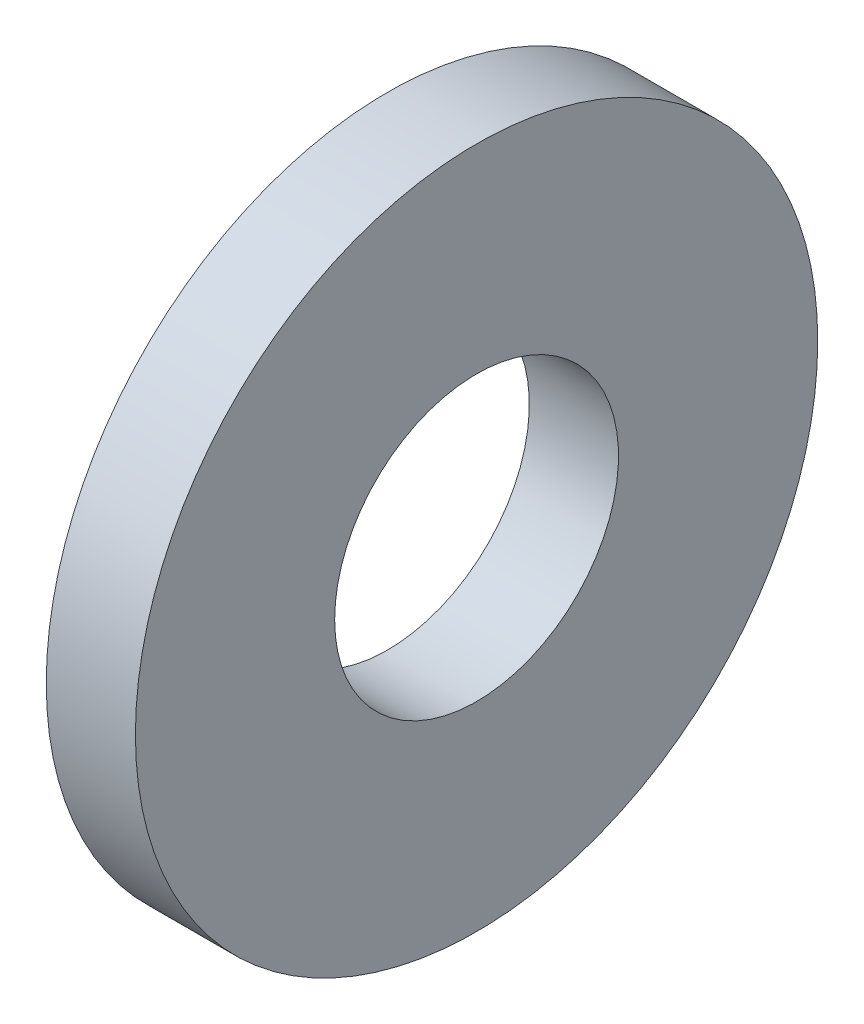
SolidWorks part; units mm, degrees
ref_plane "Plane1" through (0, 0, 0) normal (0, 0, 1) x (1, 0, 0)
ref_plane "Plane2" through (0, 0, 0) normal (0, 1, 0) x (1, 0, 0)
ref_plane "Plane3" through (0, 0, 0) normal (1, 0, 0) x (0, 0, -1)
sketch "Sketch1" plane through (0, 0, 0) normal (0, 0, 1) x (1, 0, 0)
  line L0 (-34.925, 0) -> (9.525, 0) construction
  line L1 (0, 1.9812) -> (0, 4.7625)
  line L2 (0, 4.7625) -> (-1.2446, 4.7625)
  line L3 (-1.2446, 4.7625) -> (-1.2446, 1.9812)
  line L4 (-1.2446, 1.9812) -> (0, 1.9812)
  dimension "Thickness" = 1.2446
  dimension "Inside_dia" = 3.9624
  dimension "Outside_dia" = 9.525
revolve "Base-Revolve" add sketch "Sketch1" angle 360 about L0
